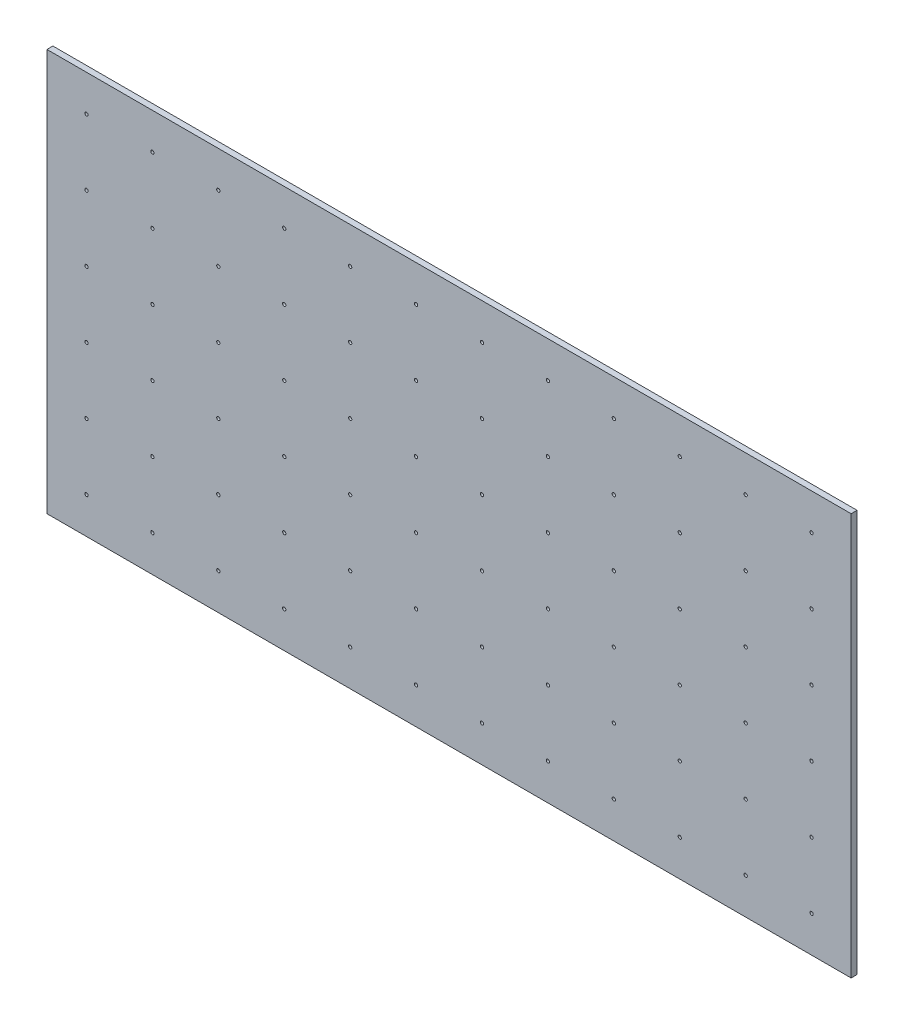
SolidWorks part; units mm, degrees
ref_plane "Front Plane" through (0, 0, 0) normal (0, 0, 1) x (1, 0, 0)
ref_plane "Top Plane" through (0, 0, 0) normal (0, 1, 0) x (1, 0, 0)
ref_plane "Right Plane" through (0, 0, 0) normal (1, 0, 0) x (0, 0, -1)
sketch "Sketch1" plane through (0, 0, 0) normal (0, 0, 1) x (1, 0, 0)
  line L0 (-1291.2062, 678.8327) -> (-1457.1305, 678.8327)
  line L1 (-1291.2062, -541.1673) -> (1148.7938, -541.1673)
  line L2 (-1291.2062, -541.1673) -> (-1291.2062, 678.8327)
  line L3 (-1291.2062, 678.8327) -> (1148.7938, 678.8327)
  line L4 (1148.7938, -541.1673) -> (1148.7938, 678.8327)
  circle A0 centre (-1171.2062, 568.8327) radius 5
  circle A1 centre (-971.2062, 568.8327) radius 5
  circle A2 centre (-771.2062, 568.8327) radius 5
  circle A3 centre (-571.2062, 568.8327) radius 5
  circle A4 centre (-371.2062, 568.8327) radius 5
  circle A5 centre (-171.2062, 568.8327) radius 5
  circle A6 centre (28.7938, 568.8327) radius 5
  circle A7 centre (228.7938, 568.8327) radius 5
  circle A8 centre (428.7938, 568.8327) radius 5
  circle A9 centre (628.7938, 568.8327) radius 5
  circle A10 centre (828.7938, 568.8327) radius 5
  circle A11 centre (1028.7938, 568.8327) radius 5
  circle A12 centre (1028.7938, 368.8327) radius 5
  circle A13 centre (1028.7938, 168.8327) radius 5
  circle A14 centre (1028.7938, -31.1673) radius 5
  circle A15 centre (1028.7938, -231.1673) radius 5
  circle A16 centre (1028.7938, -431.1673) radius 5
  circle A17 centre (828.7938, -431.1673) radius 5
  circle A18 centre (628.7938, -431.1673) radius 5
  circle A19 centre (428.7938, -431.1673) radius 5
  circle A20 centre (228.7938, -431.1673) radius 5
  circle A21 centre (28.7938, -431.1673) radius 5
  circle A22 centre (-171.2062, -431.1673) radius 5
  circle A23 centre (-371.2062, -431.1673) radius 5
  circle A24 centre (-571.2062, -431.1673) radius 5
  circle A25 centre (-771.2062, -431.1673) radius 5
  circle A26 centre (-971.2062, -431.1673) radius 5
  circle A27 centre (-1171.2062, -431.1673) radius 5
  circle A28 centre (-1171.2062, -231.1673) radius 5
  circle A29 centre (-1171.2062, -31.1673) radius 5
  circle A30 centre (-1171.2062, 168.8327) radius 5
  circle A31 centre (-1171.2062, 368.8327) radius 5
  circle A32 centre (-971.2062, 368.8327) radius 5
  circle A33 centre (-771.2062, 368.8327) radius 5
  circle A34 centre (-571.2062, 368.8327) radius 5
  circle A35 centre (-371.2062, 368.8327) radius 5
  circle A36 centre (-171.2062, 368.8327) radius 5
  circle A37 centre (28.7938, 368.8327) radius 5
  circle A38 centre (228.7938, 368.8327) radius 5
  circle A39 centre (428.7938, 368.8327) radius 5
  circle A40 centre (628.7938, 368.8327) radius 5
  circle A41 centre (828.7938, 368.8327) radius 5
  circle A42 centre (828.7938, 168.8327) radius 5
  circle A43 centre (828.7938, -31.1673) radius 5
  circle A44 centre (828.7938, -231.1673) radius 5
  circle A45 centre (628.7938, -231.1673) radius 5
  circle A46 centre (428.7938, -231.1673) radius 5
  circle A47 centre (228.7938, -231.1673) radius 5
  circle A48 centre (28.7938, -231.1673) radius 5
  circle A49 centre (-171.2062, -231.1673) radius 5
  circle A50 centre (-371.2062, -231.1673) radius 5
  circle A51 centre (-571.2062, -231.1673) radius 5
  circle A52 centre (-771.2062, -231.1673) radius 5
  circle A53 centre (-971.2062, -231.1673) radius 5
  circle A54 centre (-971.2062, -31.1673) radius 5
  circle A55 centre (-971.2062, 168.8327) radius 5
  circle A56 centre (-771.2062, 168.8327) radius 5
  circle A57 centre (-571.2062, 168.8327) radius 5
  circle A58 centre (-371.2062, 168.8327) radius 5
  circle A59 centre (-171.2062, 168.8327) radius 5
  circle A60 centre (28.7938, 168.8327) radius 5
  circle A61 centre (228.7938, 168.8327) radius 5
  circle A62 centre (428.7938, 168.8327) radius 5
  circle A63 centre (628.7938, 168.8327) radius 5
  circle A64 centre (628.7938, -31.1673) radius 5
  circle A65 centre (428.7938, -31.1673) radius 5
  circle A66 centre (228.7938, -31.1673) radius 5
  circle A67 centre (28.7938, -31.1673) radius 5
  circle A68 centre (-171.2062, -31.1673) radius 5
  circle A69 centre (-371.2062, -31.1673) radius 5
  circle A70 centre (-571.2062, -31.1673) radius 5
  circle A71 centre (-771.2062, -31.1673) radius 5
  point P41 (-1171.2062, 568.8327)
  point P42 (-971.2062, 568.8327)
  point P43 (-771.2062, 568.8327)
  point P44 (-571.2062, 568.8327)
  point P45 (-371.2062, 568.8327)
  point P46 (-171.2062, 568.8327)
  point P47 (28.7938, 568.8327)
  point P48 (228.7938, 568.8327)
  point P49 (428.7938, 568.8327)
  point P50 (628.7938, 568.8327)
  point P51 (828.7938, 568.8327)
  point P52 (1028.7938, 568.8327)
  point P53 (1028.7938, 368.8327)
  point P54 (828.7938, 368.8327)
  point P55 (628.7938, 368.8327)
  point P56 (428.7938, 368.8327)
  point P57 (228.7938, 368.8327)
  point P58 (28.7938, 368.8327)
  point P59 (-171.2062, 368.8327)
  point P60 (-371.2062, 368.8327)
  point P61 (-571.2062, 368.8327)
  point P62 (-771.2062, 368.8327)
  point P63 (-971.2062, 368.8327)
  point P64 (-1171.2062, 368.8327)
  point P65 (-1171.2062, 168.8327)
  point P66 (-971.2062, 168.8327)
  point P67 (-771.2062, 168.8327)
  point P68 (-571.2062, 168.8327)
  point P69 (-371.2062, 168.8327)
  point P70 (-171.2062, 168.8327)
  point P71 (28.7938, 168.8327)
  point P72 (228.7938, 168.8327)
  point P73 (428.7938, 168.8327)
  point P74 (628.7938, 168.8327)
  point P75 (828.7938, 168.8327)
  point P76 (1028.7938, 168.8327)
  point P77 (1028.7938, -31.1673)
  point P78 (828.7938, -31.1673)
  point P79 (628.7938, -31.1673)
  point P80 (428.7938, -31.1673)
  point P81 (228.7938, -31.1673)
  point P82 (28.7938, -31.1673)
  point P83 (-171.2062, -31.1673)
  point P84 (-371.2062, -31.1673)
  point P85 (-571.2062, -31.1673)
  point P86 (-771.2062, -31.1673)
  point P87 (-971.2062, -31.1673)
  point P88 (-1171.2062, -31.1673)
  point P89 (-1171.2062, -231.1673)
  point P90 (-971.2062, -231.1673)
  point P91 (-771.2062, -231.1673)
  point P92 (-571.2062, -231.1673)
  point P93 (-371.2062, -231.1673)
  point P94 (-171.2062, -231.1673)
  point P95 (28.7938, -231.1673)
  point P96 (228.7938, -231.1673)
  point P97 (428.7938, -231.1673)
  point P98 (628.7938, -231.1673)
  point P99 (828.7938, -231.1673)
  point P100 (1028.7938, -231.1673)
  point P101 (1028.7938, -431.1673)
  point P102 (828.7938, -431.1673)
  point P103 (628.7938, -431.1673)
  point P104 (428.7938, -431.1673)
  point P105 (228.7938, -431.1673)
  point P106 (28.7938, -431.1673)
  point P107 (-171.2062, -431.1673)
  point P108 (-371.2062, -431.1673)
  point P109 (-571.2062, -431.1673)
  point P110 (-771.2062, -431.1673)
  point P111 (-971.2062, -431.1673)
  point P112 (-1171.2062, -431.1673)
  dimension "D1" = 2440
  dimension "D2" = 1220
extrude "Boss-Extrude1" add sketch "Sketch1" along normal blind 18 contours L1 L4 L3 L2 A71 A70 A69 A68 A67 A66 A65 A64 A63 A62 A61 A60 A59 A58 A57 A56 A55 A54 A53 A52 A51 A50 A49
